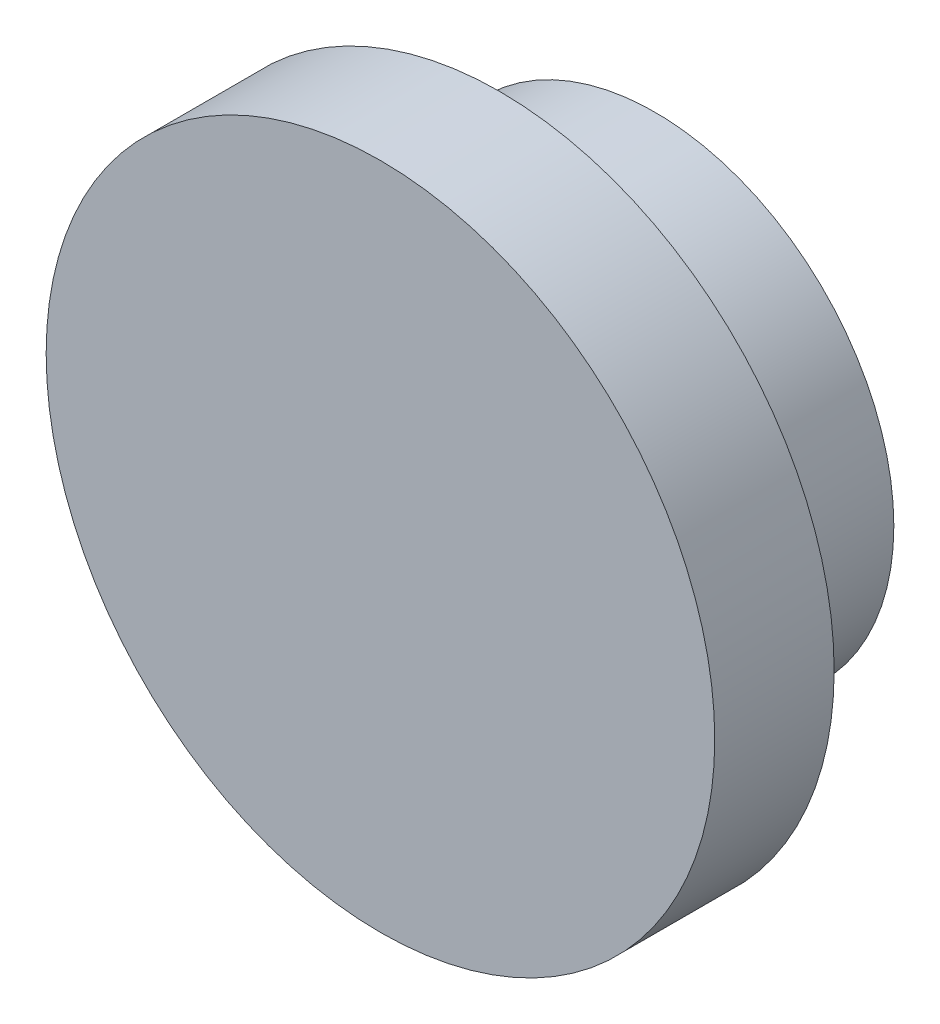
SolidWorks part; units mm, degrees
ref_plane "Front Plane" through (0, 0, 0) normal (0, 0, 1) x (1, 0, 0)
ref_plane "Top Plane" through (0, 0, 0) normal (0, 1, 0) x (1, 0, 0)
ref_plane "Right Plane" through (0, 0, 0) normal (1, 0, 0) x (0, 0, -1)
sketch "Sketch1" plane through (0, 0, 0) normal (0, 0, 1) x (1, 0, 0)
  circle A0 centre (0, 0) radius 10
  dimension "D1" = 20
extrude "Boss-Extrude1" add sketch "Sketch1" along normal blind 6.5
sketch "Sketch2" plane through (0, 0, 6.5) normal (0, 0, 1) x (1, 0, 0)
  circle A0 centre (0, 0) radius 14
  circle A1 centre (0, 0) radius 10 construction
  dimension "D1" = 4
extrude "Boss-Extrude2" add sketch "Sketch2" along normal blind 5
sketch "Sketch3" plane through (0, 0, 11.5) normal (0, 0, 1) x (1, 0, 0)
  circle A0 centre (0, 0) radius 10
  dimension "D1" = 20
